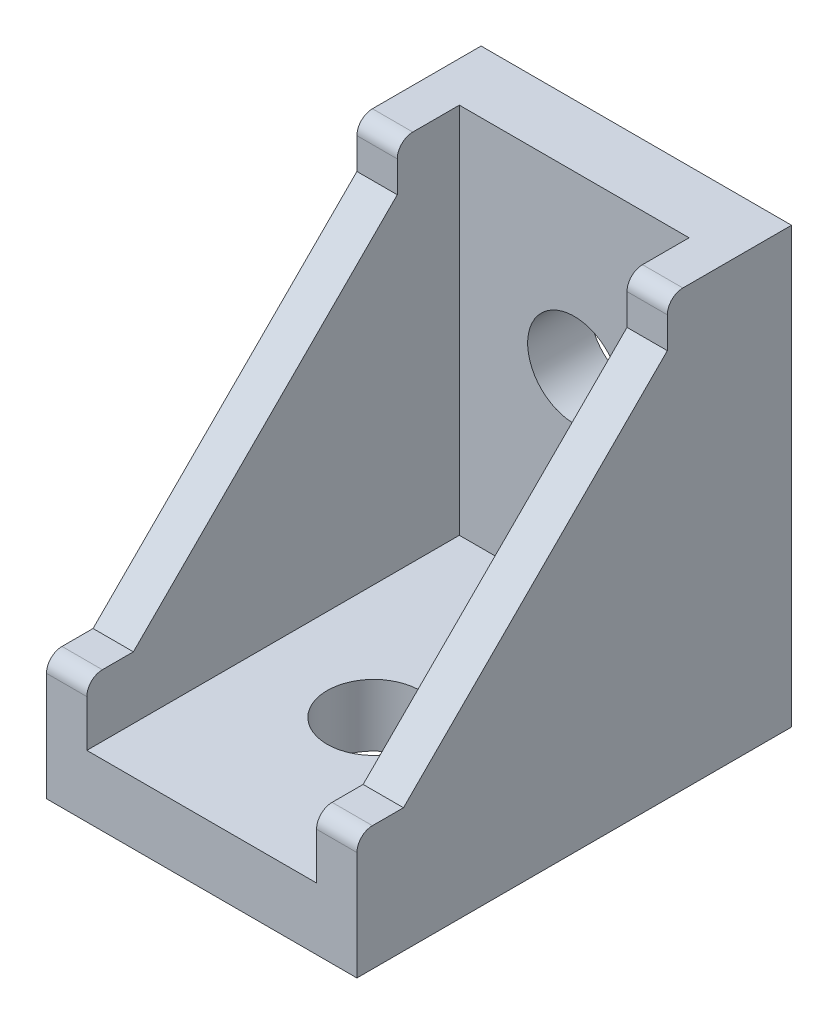
SolidWorks part; units mm, degrees
ref_plane "前视基准面" through (0, 0, 0) normal (0, 0, 1) x (1, 0, 0)
ref_plane "上视基准面" through (0, 0, 0) normal (0, 1, 0) x (1, 0, 0)
ref_plane "右视基准面" through (0, 0, 0) normal (1, 0, 0) x (0, 0, -1)
sketch "草图1" plane through (0, 0, 0) normal (0, 0, 1) x (1, 0, 0)
  line L1 (-10, 14) -> (10, 14)
  line L2 (-10, 14) -> (-10, -14)
  line L3 (-10, -14) -> (10, -14)
  line L4 (10, 14) -> (10, -14)
  line L5 (-10, 14) -> (10, -14) construction
  line L6 (-10, -14) -> (10, 14) construction
  point P0 (0, 0)
  dimension "D1" = 20
  dimension "D2" = 28
extrude "凸台-拉伸1" add sketch "草图1" along normal blind 4
sketch "草图2" plane through (0, 0, 4) normal (0, 0, 1) x (1, 0, 0)
  line L0 (10, -14) -> (10, 14) construction
  line L1 (-10, -14) -> (10, -14)
  line L2 (-10, -14) -> (-10, -10)
  line L3 (-10, -10) -> (10, -10)
  line L4 (10, -14) -> (10, -10)
  dimension "D1" = 4
extrude "凸台-拉伸2" add sketch "草图2" along normal blind 24
sketch "草图3" plane through (-10, 0, 0) normal (-1, 0, 0) x (0, 0, 1)
  line L0 (4, 14) -> (8, 14)
  line L1 (8, 14) -> (8, 11)
  line L2 (8, 11) -> (25, -6)
  line L3 (25, -6) -> (28, -6)
  line L4 (28, -6) -> (28, -10)
  line L5 (4, 14) -> (4, -10)
  line L6 (4, -10) -> (28, -10)
  dimension "D1" = 4
  dimension "D2" = 3
  dimension "D3" = 4
  dimension "D4" = 3
extrude "凸台-拉伸3" add sketch "草图3" against normal blind 2.6
mirror "镜向1" about plane through (0, 0, 0) normal (1, 0, 0) of "凸台-拉伸3"
fillet "圆角1" radius 1 4 edges at (-8.7, -6, 28) (8.7, -6, 28) (8.7, 14, 8) (-8.7, 14, 8)
sketch "草图4" plane through (0, 0, 4) normal (0, 0, 1) x (1, 0, 0)
  circle A0 centre (0, 2.9205) radius 3
  dimension "D1" = 6
extrude "切除-拉伸1" cut sketch "草图4" against normal through all
ref_plane "基准面1" through (0, -7, 7) normal (0, -0.7071, 0.7071) x (1, 0, 0)
mirror "镜向2" about plane through (0, -7, 7) normal (0, -0.7071, 0.7071) of "切除-拉伸1"
